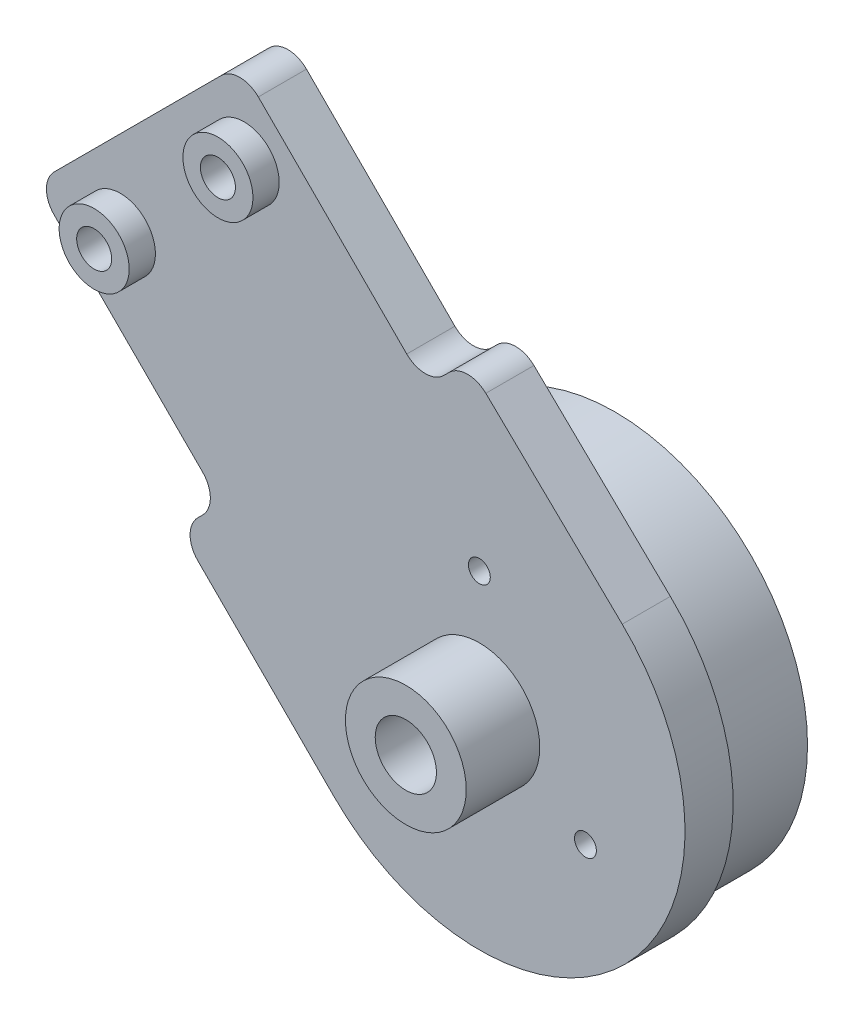
SolidWorks part; units mm, degrees
ref_plane "Front Plane" through (0, 0, 0) normal (0, 0, 1) x (1, 0, 0)
ref_plane "Top Plane" through (0, 0, 0) normal (0, 1, 0) x (1, 0, 0)
ref_plane "Right Plane" through (0, 0, 0) normal (1, 0, 0) x (0, 0, -1)
sketch "Sketch2" plane through (0, 0, 0) normal (0, 0, 1) x (1, 0, 0)
  line L0 (-100, 0) -> (100, 0) construction
  line L1 (-100, 0) -> (0, 100) construction
  line L2 (0, 100) -> (100, 0) construction
  line L3 (0, 0) -> (-52.6991, 47.3009) construction
  line L4 (-40, 60) -> (40, 60) construction
  line L5 (0, 100) -> (0, 60) construction
  circle A0 centre (-100, 0) radius 20
  circle A1 centre (0, 0) radius 20
  circle A2 centre (100, 0) radius 20
  point P2 (0, 0)
  dimension "D5" = 40
  dimension "D1" = 200
  dimension "D2" = 93.09
  dimension "D3" = 80
  dimension "D4" = 90
sketch "Sketch3" plane through (0, 0, 0) normal (0, 0, 1) x (1, 0, 0)
  line L0 (-40, 60) -> (-56.5165, 43.4835) construction
  line L1 (75.9584, 9.8995) -> (90.1005, 24.0416) construction
  line L2 (-40, 60) -> (40, 60) construction
  line L3 (40, 60) -> (86.565, 13.435) construction
  line L4 (0, 100) -> (100, 0) construction
  line L5 (86.565, 13.435) -> (40, 60) construction
  line L6 (-100, 0) -> (0, 100) construction
  line L7 (44.1421, 70) -> (93.636, 20.5061)
  line L8 (-44.1421, 70) -> (44.1421, 70)
  line L9 (-44.1421, 70) -> (-63.5876, 50.5546)
  line L10 (35.8579, 50) -> (79.4939, 6.364)
  line L11 (-35.8579, 50) -> (35.8579, 50)
  line L12 (-35.8579, 50) -> (-49.4454, 36.4124)
  line L13 (-63.5876, 50.5546) -> (-49.4454, 36.4124)
  line L14 (79.4939, 6.364) -> (93.636, 20.5061)
  line L15 (81.9688, 8.8388) -> (95.4038, -4.5962)
  line L16 (90.9809, 17.8509) -> (104.534, 4.6576)
  line L17 (-3.4304, 82.6944) -> (-6, 70)
  line L18 (0, 100) -> (0, 60) construction
  line L19 (3.4304, 82.6944) -> (6, 70)
  circle A0 centre (100, 0) radius 3.5
  circle A1 centre (100, 0) radius 10 construction
  arc A2 (95.4038, -4.5962) -> (104.534, 4.6576) centre (100, 0) ccw
  circle A3 centre (100, 0) radius 0.5
  circle A4 centre (100, 0) radius 20 construction
  circle A5 centre (100, 0) radius 6.5 construction
  circle A6 centre (79.4939, 13.435) radius 1
  circle A7 centre (86.565, 20.5061) radius 1
  circle A8 centre (0, 60) radius 1.5
  circle A11 centre (0, 82) radius 1.5
  arc A12 (3.4304, 82.6944) -> (-3.4304, 82.6944) centre (0, 82) ccw
  circle A13 centre (0, 82) radius 3.5 construction
  circle A14 centre (-52.6991, 47.3009) radius 1
  dimension "D4" = 20
  dimension "D5" = 7
  dimension "D10" = 2
  dimension "D11" = 3
  dimension "D15" = 2
  dimension "D3" = 27.5
  dimension "D8" = 19
  dimension "D9" = 5
  dimension "D12" = 2
  dimension "D14" = 6
  dimension "D13" = 6
  dimension "D16" = 5
  dimension "D17" = 5
  dimension "D18" = 12
  dimension "D1" = 10
  dimension "D2" = 10
  dimension "D6" = 3
  dimension "D7" = 3
sketch "Sketch4" plane through (0, 0, 0) normal (0, 0, 1) x (1, 0, 0)
  line L0 (-100, 0) -> (100, 0) construction
  line L1 (-88.5703, 11.4297) -> (-52.6991, 47.3009) construction
  line L2 (-100, 0) -> (0, 100) construction
  line L3 (-52.6991, 47.3009) -> (-14.1397, 12.6913) construction
  line L4 (0, 0) -> (-52.6991, 47.3009) construction
  line L5 (-79.4939, 6.364) -> (-52.3277, 33.5302)
  line L6 (-52.3277, 33.5302) -> (-20.8193, 5.2493)
  line L7 (-93.636, 20.5061) -> (-53.0706, 61.0716)
  line L8 (-53.0706, 61.0716) -> (-7.4601, 20.1332)
  line L9 (-95.6414, 18.5007) -> (-53.0706, 61.0716) construction
  line L10 (-81.4993, 4.3586) -> (-52.3277, 33.5302) construction
  line L11 (-7.4601, 20.1332) -> (-20.8193, 5.2493)
  line L13 (-79.4939, 6.364) -> (-93.636, 20.5061)
  line L14 (-91.1612, 18.0312) -> (-104.5962, 4.5962)
  line L15 (-81.9688, 8.8388) -> (-95.4038, -4.5962)
  line L16 (-9.9683, 17.3388) -> (4.2763, 4.8952)
  line L17 (-18.4815, 7.854) -> (-4.3418, -4.8373)
  line L18 (9.9995, -0.1043) -> (10.0659, -0.1623)
  line L19 (-85.2086, 28.9335) -> (-71.0665, 14.7914) construction
  line L20 (-25.2845, 9.2571) -> (-11.9252, 24.141) construction
  circle A0 centre (-100, 0) radius 10 construction
  circle A1 centre (0, 0) radius 10 construction
  circle A6 centre (-100, 0) radius 3.5
  circle A7 centre (0, 0) radius 3.5
  arc A8 (-104.5962, 4.5962) -> (-95.4038, -4.5962) centre (-100, 0) ccw
  arc A9 (-4.3418, -4.8373) -> (4.2763, 4.8952) centre (0, 0) ccw
  circle A10 centre (0, 0) radius 20 construction
  circle A11 centre (0, 0) radius 6.5 construction
  circle A12 centre (-100, 0) radius 6.5 construction
  circle A13 centre (-81.6731, 25.398) radius 1
  circle A14 centre (-74.602, 18.3269) radius 1
  circle A15 centre (-21.9447, 12.9781) radius 1
  circle A16 centre (-15.2651, 20.42) radius 1
  dimension "D1" = 20
  dimension "D2" = 7
  dimension "D10" = 5
  dimension "D13" = 2
  dimension "D7" = 19
  dimension "D8" = 19
  dimension "D9" = 5
  dimension "D11" = 5
  dimension "D12" = 5
  dimension "D14" = 6
  dimension "D3" = 3
  dimension "D4" = 3
  dimension "D5" = 10
  dimension "D6" = 10
sketch "Sketch5" plane through (0, 0, 0) normal (0, 0, 1) x (1, 0, 0)
  line L13 (-44.1421, 70) -> (44.1421, 70)
  line L14 (44.1421, 70) -> (57.8914, 80.5)
  line L16 (57.8914, 80.5) -> (57.8914, 90.5)
  line L17 (57.8914, 90.5) -> (-57.1086, 90.5)
  line L18 (-57.1086, 90.5) -> (-57.1086, 80.5)
  line L19 (-57.1086, 80.5) -> (-44.1421, 70)
  line L20 (-4, 60) -> (-4, 70)
  line L21 (4, 60) -> (4, 70)
  line L22 (-22.5, 82) -> (22.5, 82) construction
  line L23 (0, 100) -> (0, 60) construction
  line L24 (-22.5, 86.5) -> (22.5, 86.5)
  line L25 (-22.5, 77.5) -> (22.5, 77.5)
  circle A0 centre (0, 60) radius 1.5 construction
  circle A1 centre (0, 60) radius 1.5
  arc A2 (-4, 60) -> (4, 60) centre (0, 60) ccw
  circle A3 centre (0, 60) radius 4 construction
  arc A4 (-22.5, 86.5) -> (-22.5, 77.5) centre (-22.5, 82) ccw
  arc A5 (22.5, 77.5) -> (22.5, 86.5) centre (22.5, 82) ccw
  point P21 (0, 82)
  dimension "D1" = 115
  dimension "D2" = 10
  dimension "D3" = 2.5
  dimension "D4" = 45
  dimension "D5" = 9
  dimension "D6" = 4
  dimension "D7" = 141
sketch "Sketch6" plane through (0, 0, 0) normal (0, 0, 1) x (1, 0, 0)
  line L0 (74.6449, 13.5357) -> (86.3121, 25.203)
  line L1 (85.2515, 2.9291) -> (74.6449, 13.5357)
  line L3 (85.2515, 2.9291) -> (82.8527, 0.5303)
  line L4 (82.8527, 0.5303) -> (91.6915, -8.3085)
  line L6 (96.9187, 14.5964) -> (99.3045, 17.0081)
  line L7 (99.3045, 17.0081) -> (108.2952, 8.3238)
  line L9 (86.3121, 25.203) -> (96.9187, 14.5964)
  circle A0 centre (100, 0) radius 10 construction
  circle A1 centre (100, 0) radius 10
  arc A2 (91.6915, -8.3085) -> (108.1633, 8.4513) centre (100, 0) ccw
  circle A3 centre (86.565, 20.5061) radius 1 construction
  circle A4 centre (79.4939, 13.435) radius 1 construction
  circle A5 centre (86.565, 20.5061) radius 1
  circle A6 centre (79.4939, 13.435) radius 1
  circle A7 centre (100, 0) radius 11.75 construction
  dimension "D2" = 12.5
  dimension "D4" = 15
  dimension "D1" = 1.75
extrude "Boss-Extrude1" add sketch "Sketch6" along normal blind 2.75 contours L4 A2 L7 L6 L9 L0 L1 L3 A6 A5 A1
sketch "Sketch7" plane through (0, 0, 2.75) normal (0, 0, 1) x (1, 0, 0)
  circle A0 centre (100, 0) radius 10 construction
  circle A1 centre (100, 0) radius 10
extrude "Boss-Extrude2" add sketch "Sketch7" against normal blind 1
sketch "Sketch9" plane through (0, 0, 0) normal (0, 0, -1) x (-1, 0, 0)
  line L14 (-90.4541, -9.5459) -> (-80.3778, 0.5303)
  line L15 (-80.3778, 0.5303) -> (-82.7766, 2.9291)
  line L16 (-82.7766, 2.9291) -> (-72.17, 13.5357)
  line L17 (-72.17, 13.5357) -> (-86.3121, 27.6779)
  line L18 (-86.3121, 27.6779) -> (-96.912, 17.078)
  line L19 (-96.912, 17.078) -> (-99.2765, 19.4682)
  line L20 (-99.2765, 19.4682) -> (-109.3791, 9.7099)
  line L21 (-90.4541, -9.5459) -> (-80.3778, 0.5303)
  line L22 (-80.3778, 0.5303) -> (-82.7766, 2.9291)
  line L23 (-82.7766, 2.9291) -> (-72.17, 13.5357)
  line L24 (-72.17, 13.5357) -> (-86.3121, 27.6779)
  line L25 (-86.3121, 27.6779) -> (-96.912, 17.078)
  line L26 (-96.912, 17.078) -> (-99.2765, 19.4682)
  line L27 (-99.2765, 19.4682) -> (-109.3791, 9.7099)
  circle A1 centre (-100, 0) radius 10 construction
  arc A2 (-109.3791, 9.7099) -> (-90.4541, -9.5459) centre (-100, 0) ccw
  arc A3 (-109.3791, 9.7099) -> (-90.4541, -9.5459) centre (-100, 0) ccw
  circle A4 centre (-100, 0) radius 10
  circle A6 centre (-100, 0) radius 11
  dimension "D1" = 1.75
  dimension "D2" = 1
extrude "Boss-Extrude3" add sketch "Sketch9" along normal blind 5 contours A6 | A4
fillet "Fillet1" radius 1.5 6 edges at (82.8527, 0.5303, 1.375) (85.2515, 2.9291, 1.375) (74.6449, 13.5357, 1.375) (86.3121, 25.203, 1.375) (99.3045, 17.0081, 1.375) (96.9187, 14.5964, 1.375)
sketch "Sketch10" plane through (0, 0, 2.75) normal (0, 0, 1) x (1, 0, 0)
  circle A0 centre (79.4939, 13.435) radius 1 construction
  circle A1 centre (86.565, 20.5061) radius 1 construction
  circle A2 centre (79.4939, 13.435) radius 1
  circle A3 centre (86.565, 20.5061) radius 1
  circle A4 centre (79.4939, 13.435) radius 2
  circle A5 centre (86.565, 20.5061) radius 2
  dimension "D1" = 1
extrude "Boss-Extrude4" add sketch "Sketch10" along normal blind 1.5
sketch "Sketch11" plane through (0, 0, 0) normal (0, 0, 1) x (1, 0, 0)
  circle A0 centre (100, 0) radius 1.75
  dimension "D1" = 3.5
extrude "Cut-Extrude1" cut sketch "Sketch11" along normal blind 7.5
sketch "Sketch13" plane through (0, 0, 2.75) normal (0, 0, 1) x (1, 0, 0)
  circle A0 centre (100, 0) radius 3.45
  circle A1 centre (100, 0) radius 1.75 construction
  circle A2 centre (100, 0) radius 1.75
  dimension "D1" = 6.9
extrude "Boss-Extrude6" add sketch "Sketch13" along normal blind 4.2
sketch "Sketch14" plane through (0, 0, 2.75) normal (0, 0, 1) x (1, 0, 0)
  circle A0 centre (100, 7) radius 0.625
  circle A1 centre (106.0622, -3.5) radius 0.625
  circle A2 centre (93.9378, -3.5) radius 0.625
  point P8 (100, 0)
  dimension "D1" = 1.25
  dimension "D3" = 7
  dimension "D2" = 3
extrude "Cut-Extrude3" cut sketch "Sketch14" against normal blind 4.2
